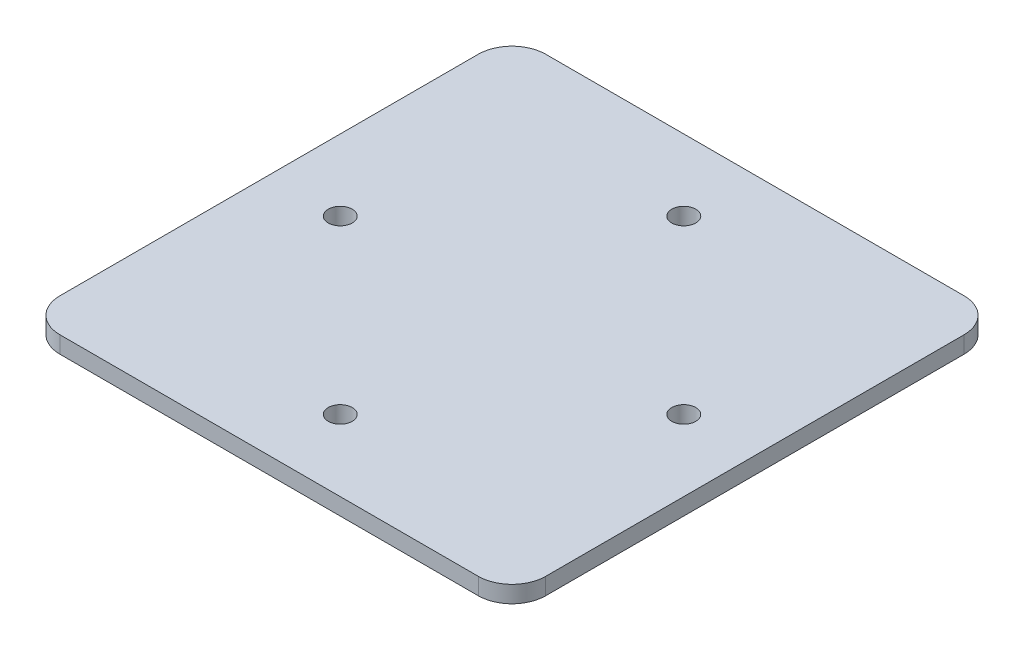
SolidWorks part; units mm, degrees
ref_plane "Front" through (0, 0, 0) normal (0, 0, 1) x (1, 0, 0)
ref_plane "Top" through (0, 0, 0) normal (0, 1, 0) x (1, 0, 0)
ref_plane "Right" through (0, 0, 0) normal (1, 0, 0) x (0, 0, -1)
sketch "Sketch1" plane through (0, 0, 0) normal (0, 1, 0) x (1, 0, 0)
  line L1 (0, 0) -> (45.72, 0)
  line L2 (0, 0) -> (0, 45.72)
  line L3 (0, 45.72) -> (45.72, 45.72)
  line L4 (45.72, 0) -> (45.72, 45.72)
  dimension "D1" = 45.72
  dimension "D2" = 45.72
extrude "Boss-Extrude1" add sketch "Sketch1" along normal blind 1.5875
fillet "Fillet1" radius 3.175 4 edges at (0, 0.7937, -45.72) (45.72, 0.7937, -45.72) (45.72, 0.7937, 0) (0, 0.7937, 0)
sketch "Sketch2" plane through (0, 1.5875, 0) normal (0, 1, 0) x (1, 0, 0)
  line L0 (44.7901, 0.9299) -> (0.9299, 44.7901) construction
  line L1 (0.9299, 0.9299) -> (44.7901, 44.7901) construction
  line L2 (45.72, 22.86) -> (0, 22.86) construction
  line L3 (45.72, 3.175) -> (45.72, 42.545) construction
  line L4 (0, 42.545) -> (0, 3.175) construction
  line L5 (22.86, 0) -> (22.86, 45.72) construction
  line L6 (3.175, 0) -> (42.545, 0) construction
  line L7 (42.545, 45.72) -> (3.175, 45.72) construction
  line L8 (39.0245, 6.6955) -> (39.0245, 39.0245) construction
  line L9 (39.0245, 6.6955) -> (6.6955, 6.6955) construction
  line L10 (6.6955, 6.6955) -> (6.6955, 39.0245) construction
  line L11 (6.6955, 39.0245) -> (39.0245, 39.0245) construction
  arc A0 (42.545, 0) -> (45.72, 3.175) centre (42.545, 3.175) ccw construction
  arc A1 (3.175, 45.72) -> (0, 42.545) centre (3.175, 42.545) ccw construction
  arc A2 (0, 3.175) -> (3.175, 0) centre (3.175, 3.175) ccw construction
  arc A3 (45.72, 42.545) -> (42.545, 45.72) centre (42.545, 42.545) ccw construction
  circle A4 centre (39.0245, 22.86) radius 1.1303
  circle A5 centre (22.86, 6.6955) radius 1.1303
  circle A6 centre (6.6955, 22.86) radius 1.1303
  circle A7 centre (22.86, 39.0245) radius 1.1303
  point P28 (39.0245, 6.6955)
  point P29 (22.86, 22.86)
  point P32 (39.0245, 22.86)
  dimension "D2" = 2.2606
  dimension "D3" = 2.2606
  dimension "D4" = 2.2606
  dimension "D5" = 2.2606
  dimension "D1" = 22.86
extrude "Cut-Extrude1" cut sketch "Sketch2" against normal through all
